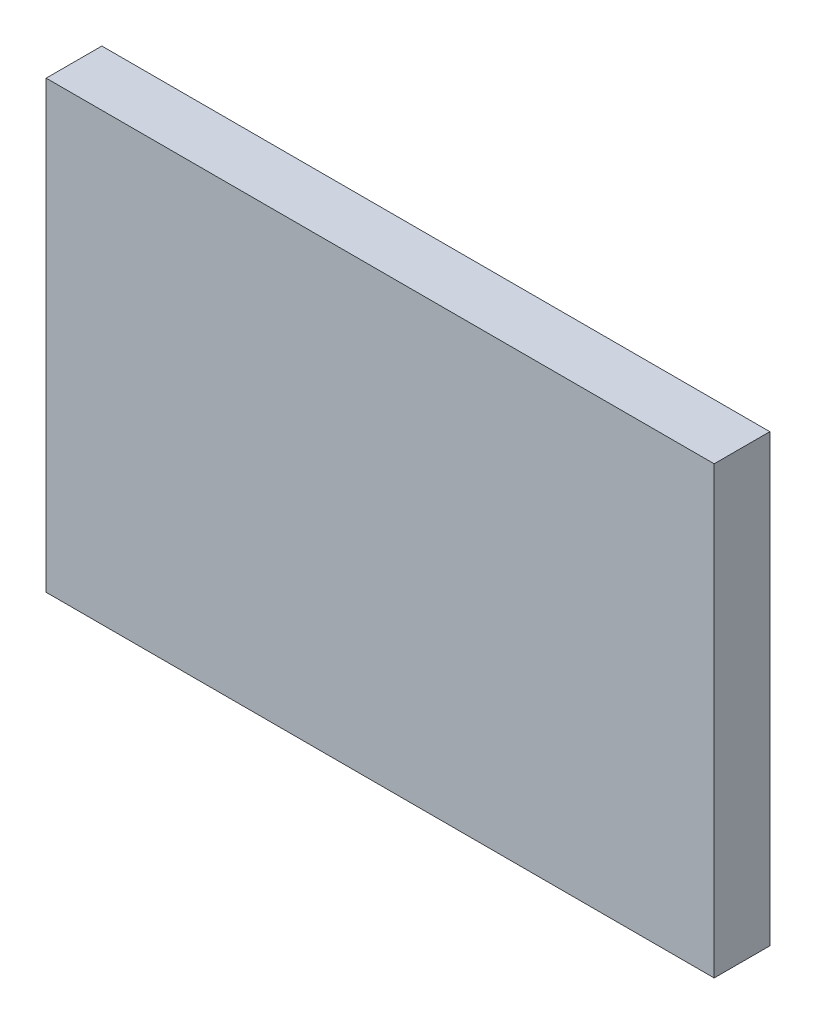
SolidWorks part; units mm, degrees
ref_plane "Front Plane" through (0, 0, 0) normal (0, 0, 1) x (1, 0, 0)
ref_plane "Top Plane" through (0, 0, 0) normal (0, 1, 0) x (1, 0, 0)
ref_plane "Right Plane" through (0, 0, 0) normal (1, 0, 0) x (0, 0, -1)
sketch "Sketch1" plane through (0, 0, 0) normal (0, 0, 1) x (1, 0, 0)
  line L1 (0, 0) -> (152.4, 0)
  line L2 (0, 0) -> (0, 101.6)
  line L3 (0, 101.6) -> (152.4, 101.6)
  line L4 (152.4, 0) -> (152.4, 101.6)
extrude "base_block" add sketch "Sketch1" along normal blind 12.7
sketch "Sketch2" plane through (0, 0, 0) normal (0, 0, 1) x (1, 0, 0)
  circle A0 centre (19.05, 19.05) radius 4.7625
sketch "Sketch3" plane through (0, 0, 0) normal (0, 0, 1) x (1, 0, 0)
  circle A0 centre (133.35, 19.05) radius 4.7625
sketch "Sketch4" plane through (0, 0, 0) normal (0, 0, 1) x (1, 0, 0)
  circle A0 centre (19.05, 82.55) radius 4.7625
sketch "Sketch5" plane through (0, 0, 0) normal (0, 0, 1) x (1, 0, 0)
  circle A0 centre (133.35, 82.55) radius 4.7625
sketch "Sketch6" plane through (0, 0, 0) normal (0, 0, 1) x (1, 0, 0)
  circle A0 centre (76.2, 50.8) radius 9.525
sketch "Sketch7" plane through (0, 0, 0) normal (0, 0, 1) x (1, 0, 0)
  line L1 (-0.254, 38.1) -> (12.446, 38.1)
  line L2 (-0.254, 38.1) -> (-0.254, 63.5)
  line L3 (-0.254, 63.5) -> (12.446, 63.5)
  line L4 (12.446, 38.1) -> (12.446, 63.5)
sketch "Sketch8" plane through (0, 0, 0) normal (0, 0, 1) x (1, 0, 0)
  line L1 (139.954, 38.1) -> (152.654, 38.1)
  line L2 (139.954, 38.1) -> (139.954, 63.5)
  line L3 (139.954, 63.5) -> (152.654, 63.5)
  line L4 (152.654, 38.1) -> (152.654, 63.5)
sketch "Sketch9" plane through (0, 0, 0) normal (0, 0, 1) x (1, 0, 0)
  line L1 (63.5, -0.254) -> (88.9, -0.254)
  line L2 (63.5, -0.254) -> (63.5, 12.446)
  line L3 (63.5, 12.446) -> (88.9, 12.446)
  line L4 (88.9, -0.254) -> (88.9, 12.446)
sketch "Sketch10" plane through (0, 0, 0) normal (0, 0, 1) x (1, 0, 0)
  line L1 (63.5, 89.154) -> (88.9, 89.154)
  line L2 (63.5, 89.154) -> (63.5, 101.854)
  line L3 (63.5, 101.854) -> (88.9, 101.854)
  line L4 (88.9, 89.154) -> (88.9, 101.854)
sketch "Sketch11" plane through (0, 0, 0) normal (0, 0, 1) x (1, 0, 0)
  circle A0 centre (31.75, 12.7) radius 2.54
sketch "Sketch12" plane through (0, 0, 0) normal (0, 0, 1) x (1, 0, 0)
  circle A0 centre (31.75, 12.7) radius 2.54
sketch "Sketch13" plane through (0, 0, 0) normal (0, 0, 1) x (1, 0, 0)
  circle A0 centre (31.75, 12.7) radius 2.54
